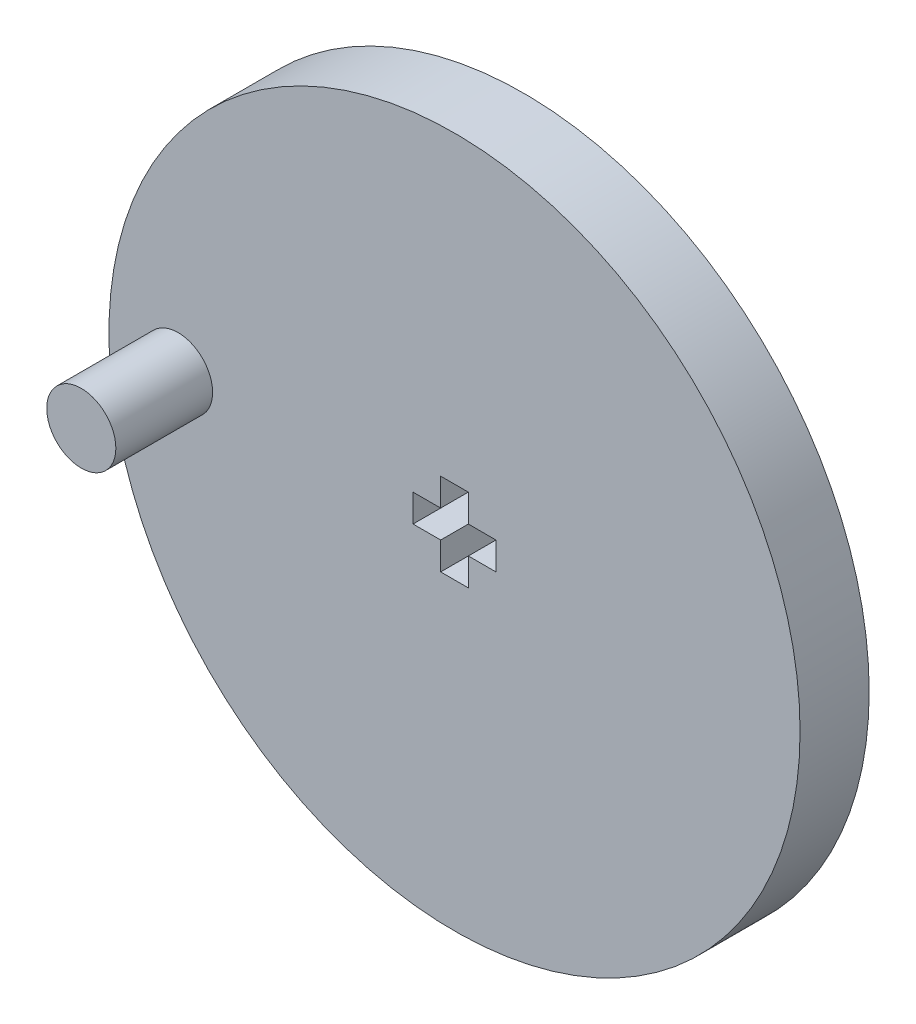
SolidWorks part; units mm, degrees
ref_plane "前视基准面" through (0, 0, 0) normal (0, 0, 1) x (1, 0, 0)
ref_plane "上视基准面" through (0, 0, 0) normal (0, 1, 0) x (1, 0, 0)
ref_plane "右视基准面" through (0, 0, 0) normal (1, 0, 0) x (0, 0, -1)
sketch "草图1" plane through (0, 0, 0) normal (0, 0, 1) x (1, 0, 0)
  circle A0 centre (0, 0) radius 25
  dimension "D1" = 50
extrude "凸台-拉伸1" add sketch "草图1" along normal blind 5
sketch "草图2" plane through (0, 0, 5) normal (0, 0, 1) x (1, 0, 0)
  circle A0 centre (0, 0) radius 20 construction
  circle A1 centre (-20, 0) radius 2.5
  dimension "D1" = 40
  dimension "D2" = 5
extrude "凸台-拉伸2" add sketch "草图2" along normal blind 7
sketch "草图3" plane through (0, 0, 5) normal (0, 0, 1) x (1, 0, 0)
  line L1 (-3, 1) -> (3, 1)
  line L2 (-3, 1) -> (-3, -1)
  line L3 (-3, -1) -> (3, -1)
  line L4 (3, 1) -> (3, -1)
  line L5 (0, -1) -> (0, 1) construction
  line L6 (-3, 0) -> (3, 0) construction
  line L7 (-1, 3) -> (1, 3)
  line L8 (-1, 3) -> (-1, -3)
  line L9 (-1, -3) -> (1, -3)
  line L10 (1, 3) -> (1, -3)
  line L11 (0, -3) -> (0, 3) construction
  line L12 (-1, 0) -> (1, 0) construction
  point P0 (0, 0)
  point P4 (0, 0)
  dimension "D1" = 6
  dimension "D2" = 6
  dimension "D3" = 2
  dimension "D4" = 2
extrude "切除-拉伸1" cut sketch "草图3" against normal through all contours L10 L7 L8 L1 | L8 L1 L2 L3 | L1 L10 L3 L4 | L10 L3 L8 L9 | L10 L1 L8 L3
